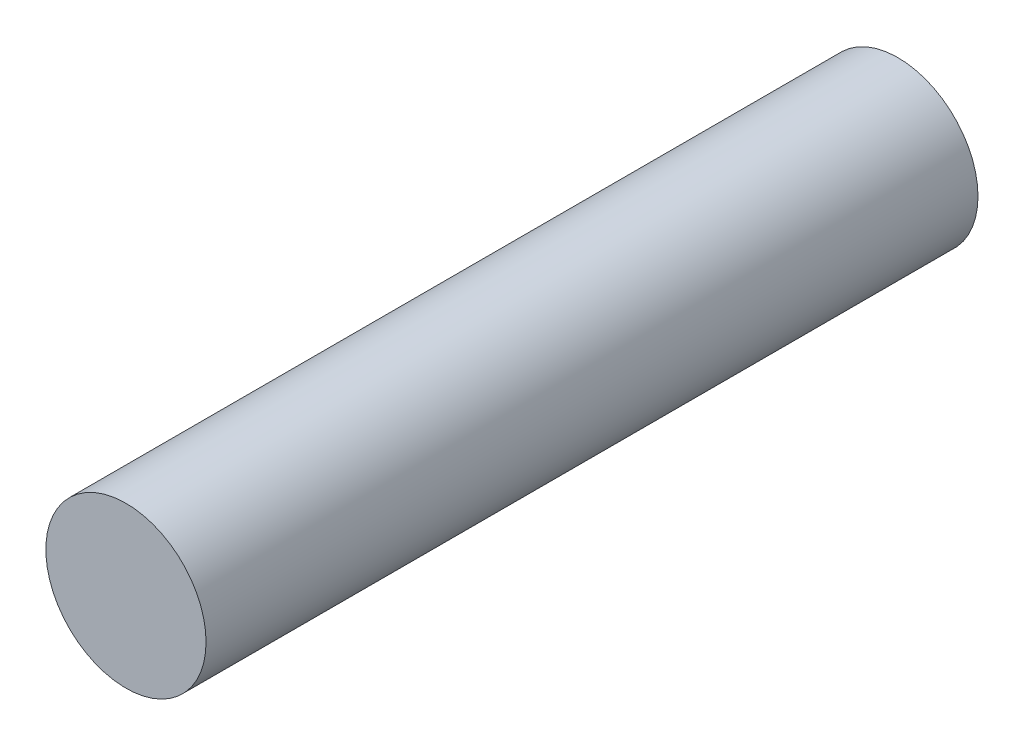
SolidWorks part; units mm, degrees
ref_plane "Plan de face" through (0, 0, 0) normal (0, 0, 1) x (1, 0, 0)
ref_plane "Plan de dessus" through (0, 0, 0) normal (0, 1, 0) x (1, 0, 0)
ref_plane "Plan de droite" through (0, 0, 0) normal (1, 0, 0) x (0, 0, -1)
sketch "Esquisse1" plane through (0, 0, 0) normal (0, 0, 1) x (1, 0, 0)
  circle A0 centre (0, 0) radius 5.5
  dimension "D1" = 11
extrude "Boss.-Extru.1" add sketch "Esquisse1" along normal blind 53
